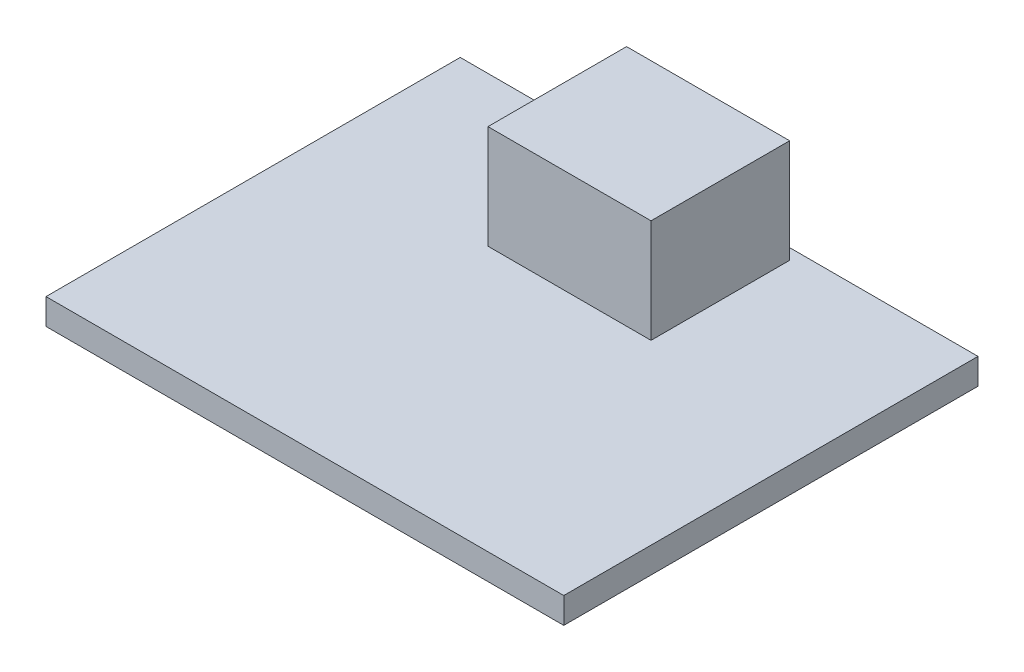
SolidWorks part; units mm, degrees
ref_plane "Front Plane" through (0, 0, 0) normal (0, 0, 1) x (1, 0, 0)
ref_plane "Top Plane" through (0, 0, 0) normal (0, 1, 0) x (1, 0, 0)
ref_plane "Right Plane" through (0, 0, 0) normal (1, 0, 0) x (0, 0, -1)
sketch "Sketch2" plane through (0, 0, 0) normal (0, 1, 0) x (1, 0, 0)
  line L1 (-63.5, -50.8) -> (63.5, -50.8)
  line L2 (-63.5, -50.8) -> (-63.5, 50.8)
  line L3 (-63.5, 50.8) -> (63.5, 50.8)
  line L4 (63.5, -50.8) -> (63.5, 50.8)
  line L5 (-63.5, -50.8) -> (63.5, 50.8) construction
  line L6 (-63.5, 50.8) -> (63.5, -50.8) construction
  point P0 (0, 0)
  dimension "D1" = 101.6
  dimension "D2" = 127
extrude "Boss-Extrude1" add sketch "Sketch2" along normal blind 6.35
sketch "Sketch3" plane through (0, 6.35, 0) normal (0, 1, 0) x (1, 0, 0)
  line L0 (0, 0) -> (0, 14.1)
  line L1 (0, 14.1) -> (0, 31.1)
  line L3 (-20, 14.1) -> (20, 14.1)
  line L4 (-20, 14.1) -> (-20, 48.1)
  line L5 (-20, 48.1) -> (20, 48.1)
  line L6 (20, 14.1) -> (20, 48.1)
  line L7 (-20, 14.1) -> (20, 48.1) construction
  line L8 (-20, 48.1) -> (20, 14.1) construction
  dimension "D1" = 14.1
  dimension "D2" = 17
  dimension "D3" = 34
  dimension "D4" = 40
extrude "Boss-Extrude2" add sketch "Sketch3" along normal blind 25.4
